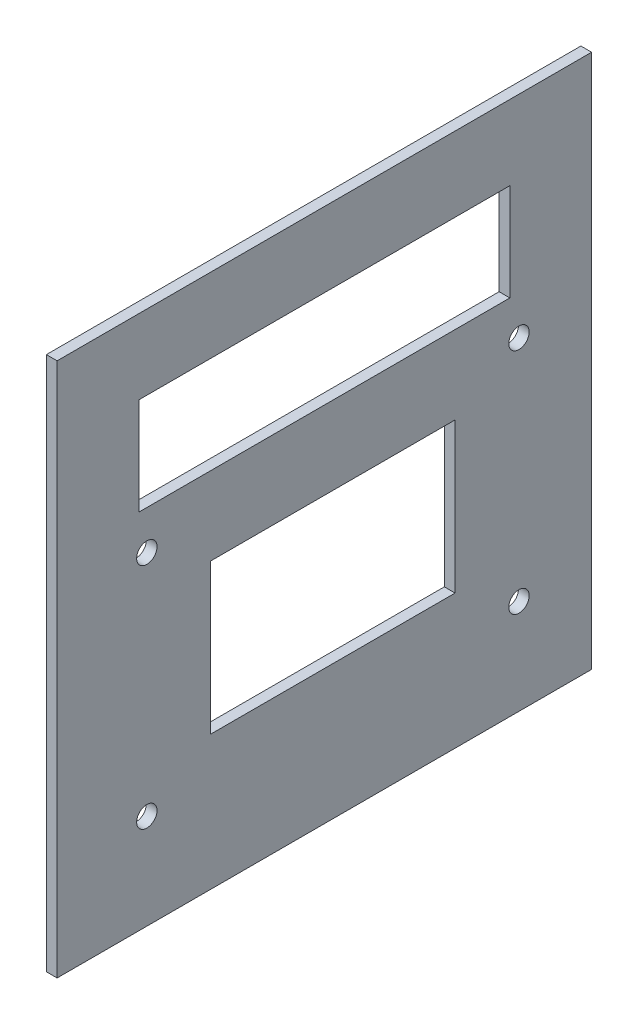
SolidWorks part; units mm, degrees
ref_plane "Front Plane" through (0, 0, 0) normal (0, 0, 1) x (1, 0, 0)
ref_plane "Top Plane" through (0, 0, 0) normal (0, 1, 0) x (1, 0, 0)
ref_plane "Right Plane" through (0, 0, 0) normal (1, 0, 0) x (0, 0, -1)
sketch "Sketch1" plane through (0, 0, 0) normal (1, 0, 0) x (0, 0, -1)
  line L1 (79, -79) -> (-79, -79)
  line L2 (79, -79) -> (79, 79)
  line L3 (79, 79) -> (-79, 79)
  line L4 (-79, -79) -> (-79, 79)
  line L5 (79, -79) -> (-79, 79) construction
  line L6 (79, 79) -> (-79, -79) construction
  line L7 (57.5211, -50.8583) -> (-52.4789, -50.8583) construction
  line L8 (57.5211, -50.8583) -> (57.5211, 16.6417) construction
  line L9 (57.5211, 16.6417) -> (-52.4789, 16.6417) construction
  line L10 (-52.4789, -50.8583) -> (-52.4789, 16.6417) construction
  line L11 (57.5211, -50.8583) -> (-52.4789, 16.6417) construction
  line L12 (57.5211, 16.6417) -> (-52.4789, -50.8583) construction
  line L14 (54.8345, 28.1798) -> (-54.8345, 28.1798)
  line L15 (54.8345, 28.1798) -> (54.8345, 56.9191)
  line L16 (54.8345, 56.9191) -> (-54.8345, 56.9191)
  line L17 (-54.8345, 28.1798) -> (-54.8345, 56.9191)
  line L18 (54.8345, 28.1798) -> (-54.8345, 56.9191) construction
  line L19 (54.8345, 56.9191) -> (-54.8345, 28.1798) construction
  line L21 (38.6377, -39.2708) -> (-33.5955, -39.2708)
  line L22 (38.6377, -39.2708) -> (38.6377, 5.0542)
  line L23 (38.6377, 5.0542) -> (-33.5955, 5.0542)
  line L24 (-33.5955, -39.2708) -> (-33.5955, 5.0542)
  line L25 (38.6377, -39.2708) -> (-33.5955, 5.0542) construction
  line L26 (38.6377, 5.0542) -> (-33.5955, -39.2708) construction
  circle A0 centre (-52.4789, 16.6417) radius 3.0156
  circle A1 centre (57.5211, 16.6417) radius 3.0156
  circle A2 centre (57.5211, -50.8583) radius 3.0156
  circle A3 centre (-52.4789, -50.8583) radius 3.0156
  point P0 (0, 0)
  point P10 (2.5211, -17.1083)
  point P17 (0, 42.5495)
  point P49 (2.5211, -17.1083)
  dimension "D1" = 158
extrude "Boss-Extrude1" add sketch "Sketch1" along normal blind 3.175
